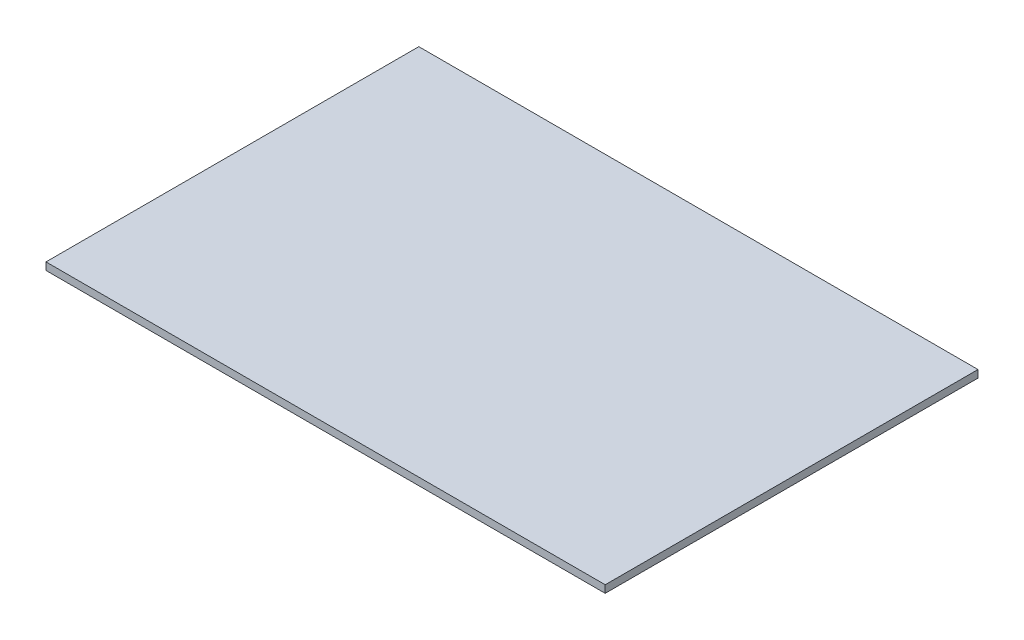
SolidWorks part; units mm, degrees
ref_plane "Front Plane" through (0, 0, 0) normal (0, 0, 1) x (1, 0, 0)
ref_plane "Top Plane" through (0, 0, 0) normal (0, 1, 0) x (1, 0, 0)
ref_plane "Right Plane" through (0, 0, 0) normal (1, 0, 0) x (0, 0, -1)
sketch "Sketch1" plane through (0, 0, 0) normal (0, 1, 0) x (1, 0, 0)
  line L2 (0, 0) -> (75, 0)
  line L3 (0, 0) -> (0, 50)
  line L4 (0, 50) -> (75, 50)
  line L5 (75, 0) -> (75, 50)
  dimension "D1" = 50
  dimension "D2" = 75
extrude "Boss-Extrude1" add sketch "Sketch1" along normal blind 1 contours L4 L5 L2 L3
